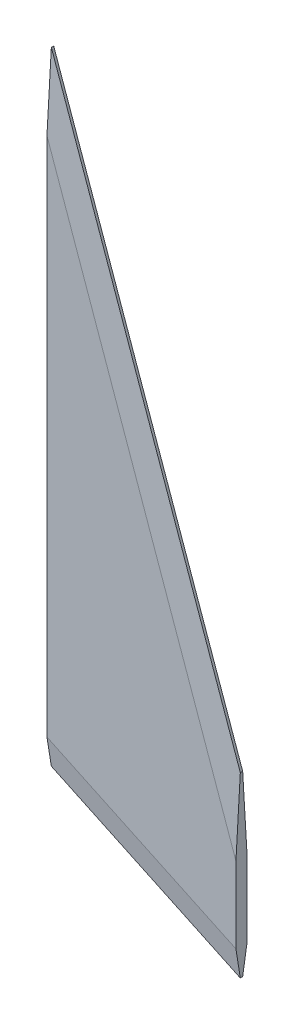
SolidWorks part; units mm, degrees
material "6061 Alloy"
ref_plane "Front Plane" through (0, 0, 0) normal (0, 0, 1) x (1, 0, 0)
ref_plane "Top Plane" through (0, 0, 0) normal (0, 1, 0) x (1, 0, 0)
ref_plane "Right Plane" through (0, 0, 0) normal (1, 0, 0) x (0, 0, -1)
sketch "Sketch1" plane through (0, 0, 0) normal (0, 0, 1) x (1, 0, 0)
  line L0 (-16.41, -60.6992) -> (-16.41, 117.1008)
  line L1 (-16.41, 117.1008) -> (37.565, -35.2992)
  line L2 (37.565, -35.2992) -> (37.565, -86.0992)
  line L3 (37.565, -86.0992) -> (-16.41, -60.6992)
extrude "Boss-Extrude1" add sketch "Sketch1" along normal mid plane 3.175
chamfer "Chamfer1" distance 1.25 angle 80 4 edges at (10.5775, -73.3992, -1.5875) (10.5775, -73.3992, 1.5875) (10.5775, 40.9008, -1.5875) (10.5775, 40.9008, 1.5875)
